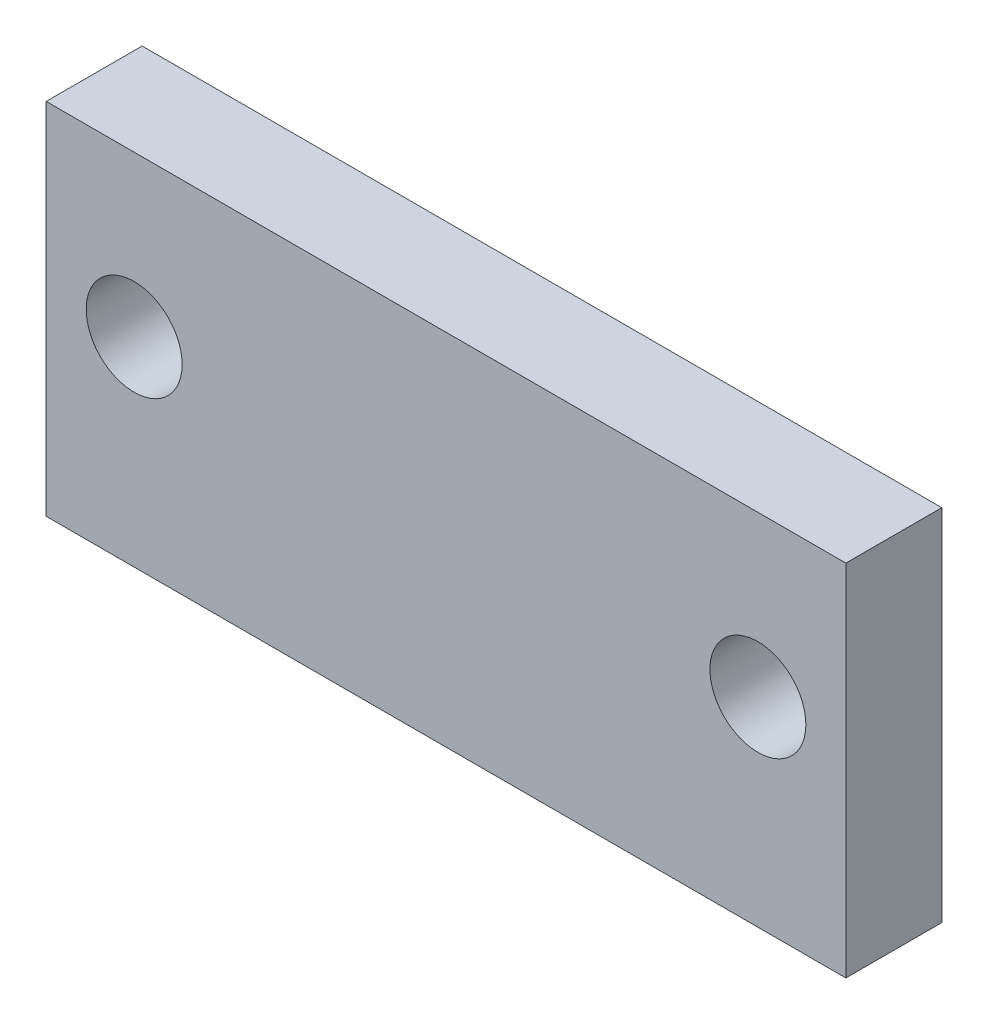
SolidWorks part; units mm, degrees
ref_plane "Front Plane" through (0, 0, 0) normal (0, 0, 1) x (1, 0, 0)
ref_plane "Top Plane" through (0, 0, 0) normal (0, 1, 0) x (1, 0, 0)
ref_plane "Right Plane" through (0, 0, 0) normal (1, 0, 0) x (0, 0, -1)
sketch "Sketch1" plane through (0, 0, 0) normal (0, 0, 1) x (1, 0, 0)
  line L1 (-12.5, -5.6168) -> (12.5, -5.6168)
  line L2 (-12.5, -5.6168) -> (-12.5, 5.6168)
  line L3 (-12.5, 5.6168) -> (12.5, 5.6168)
  line L4 (12.5, -5.6168) -> (12.5, 5.6168)
  line L5 (-12.5, -5.6168) -> (12.5, 5.6168) construction
  line L6 (-12.5, 5.6168) -> (12.5, -5.6168) construction
  point P0 (0, 0)
  dimension "D1" = 25
  dimension "D2" = 11.2337
extrude "Boss-Extrude1" add sketch "Sketch1" along normal blind 3
sketch "Sketch2" plane through (0, 0, 3) normal (0, 0, 1) x (1, 0, 0)
  line L0 (12.5, 5.6168) -> (-12.5, 5.6168) construction
  circle A0 centre (-9.75, 0.6168) radius 1.5
  circle A1 centre (9.75, 0.6168) radius 1.5
  dimension "D1" = 3
  dimension "D2" = 3
  dimension "D3" = 19.5
  dimension "D4" = 9.75
  dimension "D5" = 5
  dimension "D6" = 5
extrude "Cut-Extrude1" cut sketch "Sketch2" against normal through all
